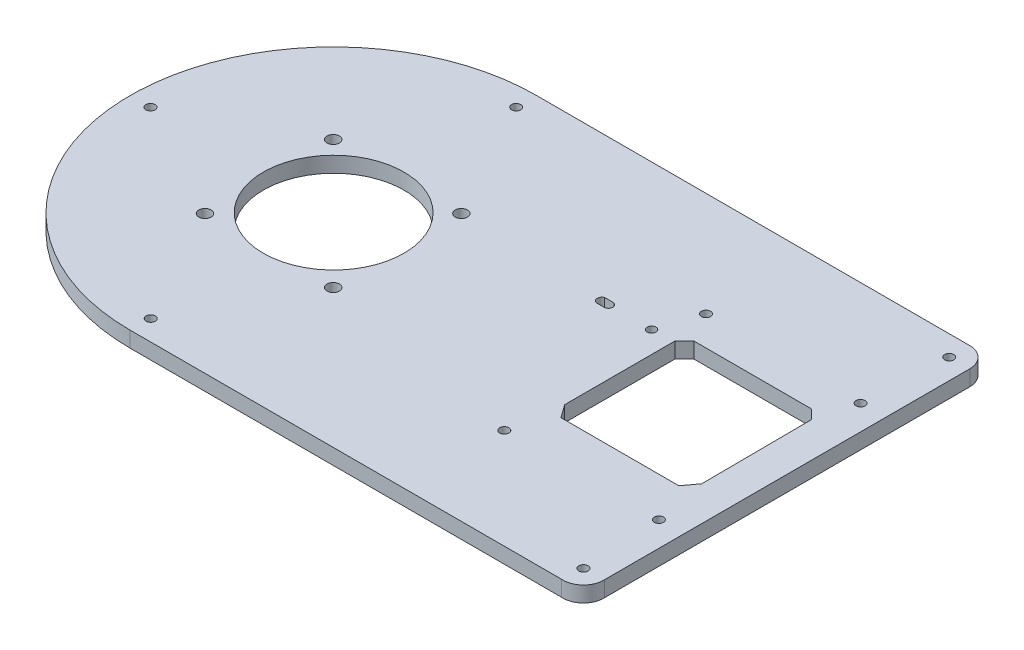
SolidWorks part; units mm, degrees
ref_plane "Front Plane" through (0, 0, 0) normal (0, 0, 1) x (1, 0, 0)
ref_plane "Top Plane" through (0, 0, 0) normal (0, 1, 0) x (1, 0, 0)
ref_plane "Right Plane" through (0, 0, 0) normal (1, 0, 0) x (0, 0, -1)
sketch "Sketch2" plane through (0, 0, 0) normal (0, 1, 0) x (1, 0, 0)
  line L1 (-52.202, 61.0827) -> (85.798, 61.0827)
  line L2 (92.798, 54.7477) -> (92.798, -62.2523)
  line L3 (85.798, -68.9173) -> (-52.202, -68.9173)
  arc A0 (85.798, 61.0827) -> (92.798, 54.7477) centre (86.2996, 54.6021) cw
  arc A1 (92.798, -62.2523) -> (85.798, -68.9173) centre (86.2996, -62.4357) cw
  arc A2 (-52.202, 61.0827) -> (-52.202, -68.9173) centre (-52.202, -3.9173) ccw
  dimension "D7" = 65
  dimension "D8" = 6.5
  dimension "D9" = 6.501
  dimension "D1" = 145
  dimension "D2" = 130
  dimension "D3" = 117
  dimension "D4" = 138
  dimension "D5" = 138
  dimension "D6" = 145
extrude "Boss-Extrude1" add sketch "Sketch2" along normal blind 5
sketch "Sketch3" plane through (0, 5, 0) normal (0, 1, 0) x (1, 0, 0)
  line L0 (-117.202, -3.9173) -> (92.798, -3.7523) construction
  line L1 (92.798, -62.2523) -> (92.798, 54.7477) construction
  line L5 (-52.202, -68.9173) -> (85.798, -68.9173) construction
  arc A0 (-52.202, 61.0827) -> (-52.202, -68.9173) centre (-52.202, -3.9173) ccw construction
  circle A1 centre (86.298, 54.5827) radius 1.475
  circle A2 centre (-52.202, 54.5827) radius 1.475
  circle A3 centre (-110.702, -3.9122) radius 1.475
  circle A4 centre (86.298, -62.4173) radius 1.475
  circle A5 centre (-52.1102, -62.4173) radius 1.475
  dimension "D1" = 58.5
  dimension "D2" = 2.95
  dimension "D4" = 6.5
  dimension "D5" = 2.95
  dimension "D6" = 6.5
  dimension "D7" = 2.95
  dimension "D8" = 2.95
  dimension "D9" = 2.95
  dimension "138.5" = 138.5
  dimension "D3" = 6.5
extrude "Cut-Extrude1" cut sketch "Sketch3" against normal through all
sketch "Sketch4" plane through (0, 5, 0) normal (0, 1, 0) x (1, 0, 0)
  line L6 (37.9384, 15.2485) -> (37.9384, -20.0602)
  line L7 (40.9384, -24.2623) -> (78.6575, -24.2623)
  line L8 (81.5426, 15.2485) -> (81.7723, -20.0602)
  line L9 (40.9384, 18.2377) -> (78.6575, 18.2377)
  line L10 (37.9384, 15.2485) -> (40.9384, 18.2377)
  line L11 (78.6575, 18.2377) -> (81.5426, 15.2485)
  line L12 (81.7723, -20.0602) -> (78.6575, -24.2623)
  line L13 (40.9384, -24.2623) -> (37.9384, -20.0602)
  line L16 (17.448, 24.3612) -> (17.448, 4.9705) construction
  line L17 (31.048, 9.3911) -> (31.048, 27.6767) construction
  line L18 (17.448, 16.028) -> (14.648, 16.028)
  line L19 (17.448, 13.228) -> (14.648, 13.228)
  circle A1 centre (-52.202, -3.822) radius 22.5
  circle A2 centre (-72.5388, 16.367) radius 1.975
  circle A6 centre (31.048, 14.628) radius 1.4
  circle A7 centre (35.4096, 27.6767) radius 1.475
  arc A8 (14.648, 16.028) -> (14.648, 13.228) centre (15.1917, 14.628) ccw
  arc A9 (17.448, 16.028) -> (17.448, 13.228) centre (17.2352, 14.628) cw
  circle A10 centre (84.8754, 27.6767) radius 1.475
  circle A11 centre (84.8754, -36.8488) radius 1.475
  circle A12 centre (35.4096, -36.8488) radius 1.475
  circle A13 centre (-72.5384, -24.643) radius 1.975
  circle A14 centre (-31.5291, -24.643) radius 1.975
  circle A15 centre (-31.5288, 16.367) radius 1.975
  point P0 (59.798, -24.2623)
  point P6 (81.6575, -2.4059)
  point P7 (37.9384, -2.4059)
  dimension "D2" = 45
  dimension "D5" = 3.95
  dimension "D6" = 2.8
  dimension "D10" = 2.8
  dimension "D12" = 2.95
  dimension "D13" = 41.01
  dimension "D14" = 3.95
  dimension "D17" = 3.95
  dimension "D18" = 3.95
  dimension "D19" = 2.95
  dimension "D20" = 2.95
  dimension "D21" = 2.95
  dimension "D3" = 3
  dimension "D4" = 42.5
  dimension "D7" = 83.25
  dimension "D8" = 18.45
  dimension "D9" = 13.6
  dimension "D11" = 2.8
  dimension "D15" = 41.01
  dimension "D16" = 112
extrude "Cut-Extrude2" cut sketch "Sketch4" against normal through all
